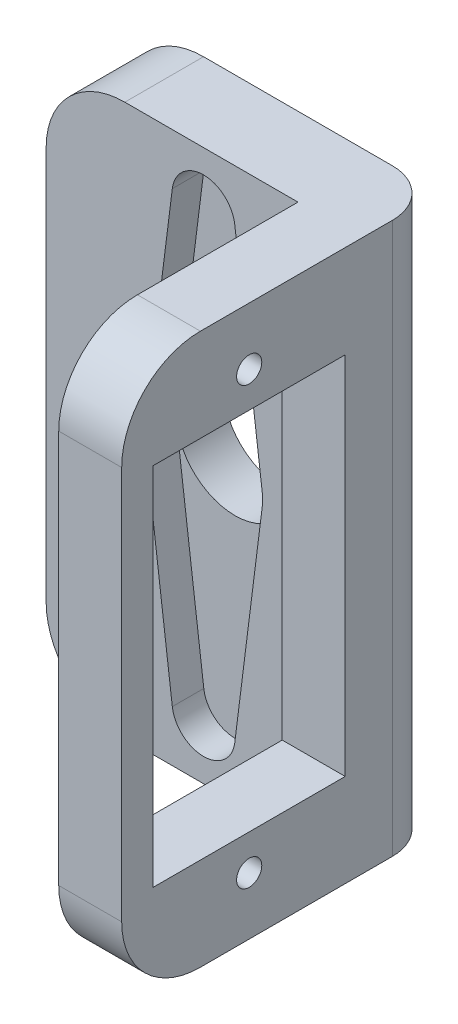
SolidWorks part; units mm, degrees
ref_plane "Front Plane" through (0, 0, 0) normal (0, 0, 1) x (1, 0, 0)
ref_plane "Top Plane" through (0, 0, 0) normal (0, 1, 0) x (1, 0, 0)
ref_plane "Right Plane" through (0, 0, 0) normal (1, 0, 0) x (0, 0, -1)
sketch "Sketch1" plane through (0, 0, 0) normal (0, 0, 1) x (1, 0, 0)
  line L0 (0, 0) -> (0, 14) construction
  line L1 (0, 0) -> (0, -14) construction
  line L2 (-3.7206, 0.4687) -> (-1.9843, 14.25) construction
  line L3 (10, -17.5) -> (-5, -17.5)
  line L4 (10, -17.5) -> (10, 17.5)
  line L5 (10, 17.5) -> (-5, 17.5)
  line L6 (-10, -12.5) -> (-10, 12.5)
  line L7 (10, -17.5) -> (-10, 17.5) construction
  line L8 (10, 17.5) -> (-10, -17.5) construction
  line L9 (-3.7206, -0.4687) -> (-1.9843, -14.25) construction
  line L10 (1.9843, -14.25) -> (3.7206, -0.4687) construction
  line L11 (1.9843, 14.25) -> (3.7206, 0.4687) construction
  arc A0 (-3.7206, 0.4687) -> (-3.7206, -0.4687) centre (0, 0) ccw construction
  arc A1 (1.9843, 14.25) -> (-1.9843, 14.25) centre (0, 14) ccw construction
  arc A2 (-1.9843, -14.25) -> (1.9843, -14.25) centre (0, -14) ccw construction
  arc A3 (-5, -17.5) -> (-10, -12.5) centre (-5, -12.5) cw
  arc A4 (-5, 17.5) -> (-10, 12.5) centre (-5, 12.5) ccw
  arc A5 (3.7206, -0.4687) -> (3.7206, 0.4687) centre (0, 0) ccw construction
  circle A6 centre (0, 0) radius 3.75
  dimension "D1" = 5
  dimension "D3" = 2
  dimension "D4" = 3.75
  dimension "D5" = 2
  dimension "D7" = 7.5
  dimension "D2" = 14
  dimension "D6" = 14
  dimension "D8" = 35
  dimension "D9" = 20
extrude "Boss-Extrude1" add sketch "Sketch1" against normal blind 5
sketch "Sketch3" plane through (0, 0, 0) normal (0, 0, 1) x (1, 0, 0)
  line L0 (0, 0) -> (-8.7328, 0) construction
  line L1 (0, 0) -> (0, 14) construction
  line L2 (0, 0) -> (6.3077, 0) construction
  line L3 (0, 0) -> (0, -14) construction
  line L4 (-1.9843, 14.25) -> (-3.7206, 0.4688)
  line L5 (-3.7206, -0.4688) -> (-1.9843, -14.25)
  line L6 (1.9843, 14.25) -> (3.7206, 0.4688)
  line L7 (1.9843, -14.25) -> (3.7206, -0.4687)
  arc A0 (1.9843, 14.25) -> (-1.9843, 14.25) centre (0, 14) ccw
  arc A1 (-1.9843, -14.25) -> (1.9843, -14.25) centre (0, -14) ccw
  arc A2 (-3.7206, 0.4688) -> (-3.7206, -0.4688) centre (0, 0) ccw
  arc A3 (3.7206, -0.4687) -> (3.7206, 0.4688) centre (0, 0) ccw
  dimension "D2" = 4
  dimension "D3" = 4
  dimension "D4" = 7.5
  dimension "D1" = 14
extrude "Cut-Extrude2" cut sketch "Sketch3" against normal blind 2
sketch "Sketch5" plane through (10, 0, 0) normal (1, 0, 0) x (0, 0, -1)
  line L0 (5, -17.5) -> (0, -17.5) construction
  line L1 (5, 17.5) -> (-10.2, 17.5)
  line L2 (5, 17.5) -> (5, -17.5)
  line L3 (5, -17.5) -> (-10.2, -17.5)
  line L4 (-15.2, 12.5) -> (-15.2, -12.5)
  line L5 (-7.1, 0) -> (-15.2, 0) construction
  line L6 (-7.1, 13.85) -> (-7.1, -13.85) construction
  line L7 (-13.2, -11.6) -> (-1, -11.6)
  line L8 (-13.2, -11.6) -> (-13.2, 11.6)
  line L9 (-13.2, 11.6) -> (-1, 11.6)
  line L10 (-1, -11.6) -> (-1, 11.6)
  line L11 (-13.2, -11.6) -> (-1, 11.6) construction
  line L12 (-13.2, 11.6) -> (-1, -11.6) construction
  line L13 (0, -17.5) -> (0, 17.5) construction
  circle A0 centre (-7.1, 13.85) radius 0.8
  circle A1 centre (-7.1, -13.85) radius 0.8
  arc A2 (-15.2, -12.5) -> (-10.2, -17.5) centre (-10.2, -12.5) ccw
  arc A3 (-15.2, 12.5) -> (-10.2, 17.5) centre (-10.2, 12.5) cw
  point P7 (-7.1, 0)
  point P16 (-7.1, 0)
  point P19 (-6.8431, 0)
  dimension "D4" = 1.6
  dimension "D6" = 5
  dimension "D1" = 12.2
  dimension "D2" = 23.2
  dimension "D3" = 2
  dimension "D5" = 27.7
  dimension "D7" = 1
extrude "Boss-Extrude2" add sketch "Sketch5" against normal blind 4
fillet "Fillet1" radius 3 1 edges at (10, 0, -5)
